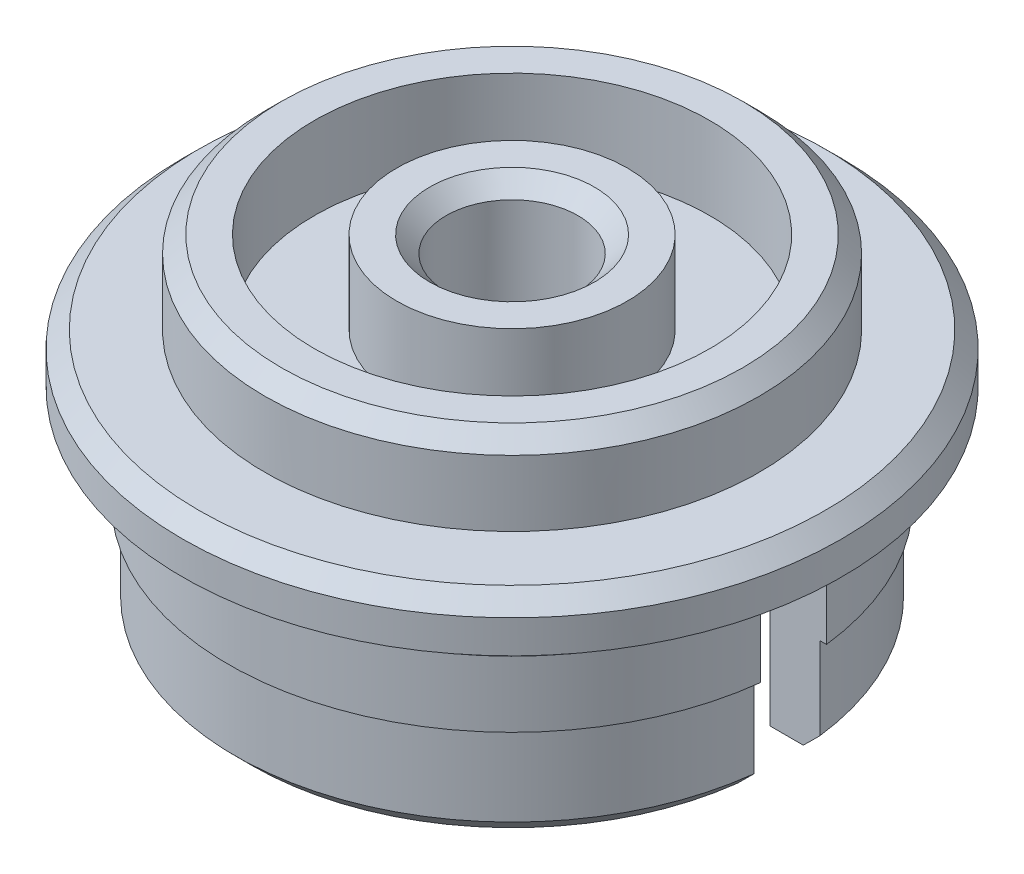
SolidWorks part; units mm, degrees
ref_plane "前视基准面" through (0, 0, 0) normal (0, 0, 1) x (1, 0, 0)
ref_plane "上视基准面" through (0, 0, 0) normal (0, 1, 0) x (1, 0, 0)
ref_plane "右视基准面" through (0, 0, 0) normal (1, 0, 0) x (0, 0, -1)
sketch "草图1" plane through (0, 0, 0) normal (0, 0, 1) x (1, 0, 0)
  line L0 (0, 0) -> (7.5, 0)
  line L1 (7.5, 0) -> (7.5, -2.5)
  line L2 (7.5, -2.5) -> (10, -2.5)
  line L3 (10, -2.5) -> (10, -4)
  line L4 (10, -4) -> (8.4, -4)
  line L5 (8.4, -4) -> (8.4, -5)
  line L6 (8.4, -5) -> (8.6, -5)
  line L7 (8.6, -5) -> (8.6, -7)
  line L8 (8.6, -7) -> (8.4, -7)
  line L9 (8.4, -7) -> (8.4, -10)
  line L10 (8.4, -10) -> (0, -10)
  line L11 (0, -10) -> (0, 0)
  dimension "D1" = 7.5
  dimension "D2" = 2.5
  dimension "D3" = 2.5
  dimension "D4" = 1.5
  dimension "D5" = 8.4
  dimension "D6" = 3
  dimension "D7" = 10
  dimension "D8" = 0.2
  dimension "D9" = 2
  dimension "D10" = 0.2
revolve "旋转1" add sketch "草图1" angle 360 about L11
sketch "草图2" plane through (0, 0, 0) normal (0, 1, 0) x (1, 0, 0)
  circle A0 centre (0, 0) radius 6
  circle A1 centre (0, 0) radius 3.5
  dimension "D1" = 12
  dimension "D2" = 7
extrude "切除-拉伸1" cut sketch "草图2" against normal blind 2.5
sketch "草图3" plane through (0, -10, 0) normal (0, -1, 0) x (1, 0, 0)
  circle A0 centre (0, 0) radius 6.9
  circle A1 centre (0, 0) radius 5
  dimension "D1" = 13.8
  dimension "D2" = 10
extrude "切除-拉伸2" cut sketch "草图3" against normal blind 6
sketch "草图4" plane through (0, -10, 0) normal (0, -1, 0) x (1, 0, 0)
  circle A0 centre (0, 0) radius 3.5
  dimension "D1" = 7
extrude "切除-拉伸3" cut sketch "草图4" against normal blind 6
sketch "草图5" plane through (0, 0, 0) normal (0, 1, 0) x (1, 0, 0)
  circle A0 centre (0, 0) radius 2
  dimension "D1" = 4
extrude "切除-拉伸4" cut sketch "草图5" against normal up to next
sketch "草图6" plane through (0, -10, 0) normal (0, -1, 0) x (1, 0, 0)
  line L0 (-9, 0) -> (9, 0) construction
  line L1 (-8.9443, -1) -> (-5.9161, -1)
  line L2 (-8.9443, 1) -> (-5.9161, 1)
  line L3 (5.9161, 1) -> (8.9443, 1)
  line L4 (-9, 1) -> (9, 1) construction
  line L5 (-9, -1) -> (9, -1) construction
  line L6 (5.9161, -1) -> (8.9443, -1)
  arc A0 (-5.9161, 1) -> (-5.9161, -1) centre (0, 0) ccw
  arc A1 (8.9443, -1) -> (8.9443, 1) centre (0, 0) ccw
  arc A2 (5.9161, -1) -> (5.9161, 1) centre (0, 0) ccw
  arc A3 (-8.9443, 1) -> (-8.9443, -1) centre (0, 0) ccw
  dimension "D1" = 12
  dimension "D2" = 18
  dimension "D3" = 1
  dimension "D4" = 1
extrude "切除-拉伸5" cut sketch "草图6" against normal blind 6
chamfer "倒角1" distance 0.5 angle 45 5 edges at (0, 0, 2) (0, 0, -7.5) (0, -2.5, -10) (0, -10, -8.4) (0, -10, 8.4)
